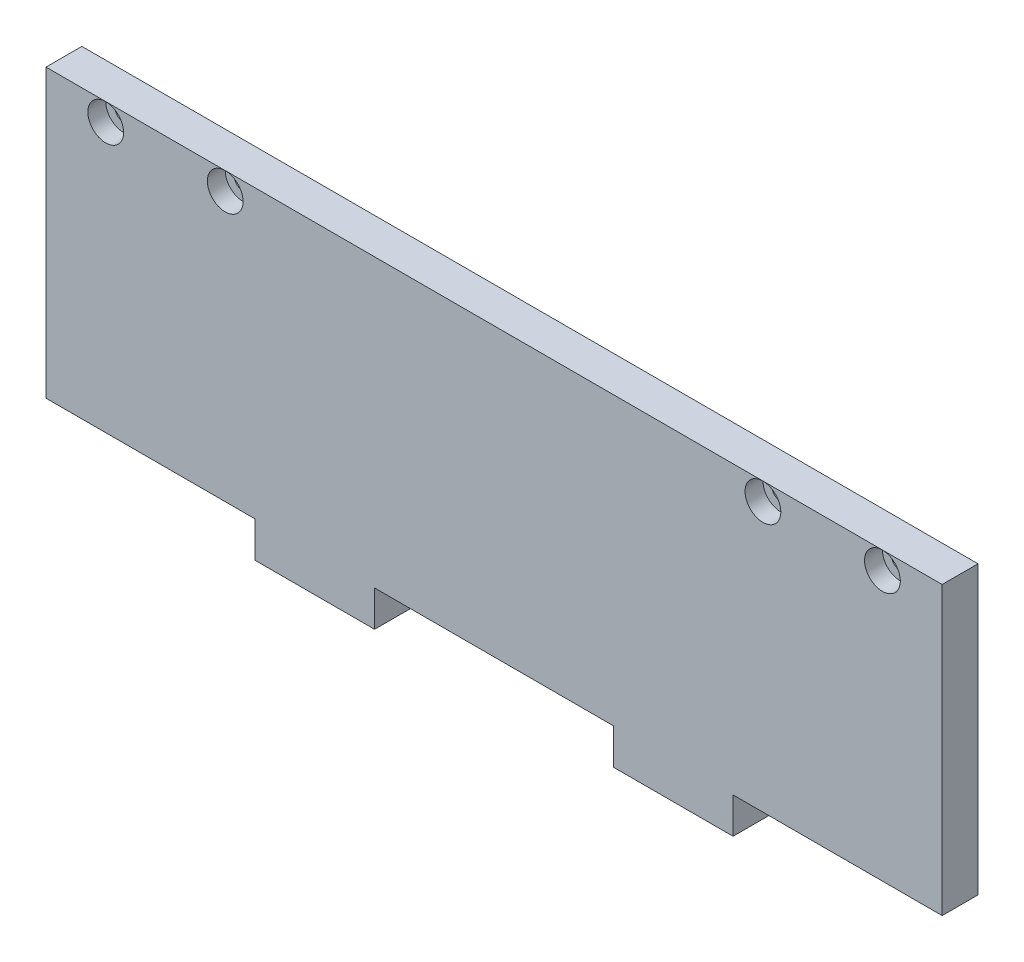
SolidWorks part; units mm, degrees
ref_plane "Plan de face" through (0, 0, 0) normal (0, 0, 1) x (1, 0, 0)
ref_plane "Plan de dessus" through (0, 0, 0) normal (0, 1, 0) x (1, 0, 0)
ref_plane "Plan de droite" through (0, 0, 0) normal (1, 0, 0) x (0, 0, -1)
sketch "Esquisse1" plane through (0, 0, 0) normal (0, 0, 1) x (1, 0, 0)
  line L1 (0, 0) -> (-150, 0)
  line L2 (0, 0) -> (0, 54)
  line L3 (0, 54) -> (-150, 54)
  line L4 (-150, 0) -> (-150, 54)
  dimension "D1" = 150
  dimension "D2" = 54
extrude "Boss.-Extru.1" add sketch "Esquisse1" along normal blind 6
sketch "Esquisse2" plane through (0, 0, 6) normal (0, 0, 1) x (1, 0, 0)
  line L1 (-150, 0) -> (0, 0) construction
  line L2 (0, 0) -> (-35, 0)
  line L3 (0, 0) -> (0, 6)
  line L4 (0, 6) -> (-35, 6)
  line L6 (-35, 0) -> (-35, 6)
  line L7 (-95, 0) -> (-55, 0)
  line L8 (-95, 0) -> (-95, 6)
  line L9 (-95, 6) -> (-55, 6)
  line L11 (-55, 0) -> (-55, 6)
  line L12 (-150, 0) -> (-115, 0)
  line L13 (-150, 0) -> (-150, 6)
  line L14 (-150, 6) -> (-115, 6)
  line L15 (-115, 0) -> (-115, 6)
  dimension "D1" = 6
  dimension "D2" = 20
  dimension "D3" = 20
  dimension "D4" = 6
  dimension "D5" = 6
  dimension "D6" = 35
  dimension "D7" = 35
extrude "Enlèv. mat.-Extru.1" cut sketch "Esquisse2" against normal through all
sketch "Esquisse4" plane through (0, 0, 6) normal (0, 0, 1) x (1, 0, 0)
  line L0 (0, 54) -> (-150, 54) construction
  line L1 (-150, 54) -> (-150, 6) construction
  line L2 (-75, 54) -> (-75, 6) construction
  line L3 (-55, 6) -> (-95, 6) construction
  circle A0 centre (-140, 51) radius 1.5
  circle A1 centre (-120, 51) radius 1.5
  circle A2 centre (-30, 51) radius 1.5
  circle A3 centre (-10, 51) radius 1.5
  dimension "D1" = 3
  dimension "D2" = 3
  dimension "D3" = 3
  dimension "D4" = 3
  dimension "D5" = 10
  dimension "D6" = 20
extrude "Enlèv. mat.-Extru.3" cut sketch "Esquisse4" against normal blind 6
sketch "Esquisse5" plane through (0, 0, 6) normal (0, 0, 1) x (1, 0, 0)
  line L0 (-75, 54) -> (-75, 6) construction
  line L1 (0, 54) -> (-150, 54) construction
  line L2 (-55, 6) -> (-95, 6) construction
  circle A0 centre (-140, 51) radius 2.995
  circle A1 centre (-120, 51) radius 2.995
  circle A2 centre (-30, 51) radius 2.995
  circle A3 centre (-10, 51) radius 2.995
  dimension "D1" = 5.99
  dimension "D2" = 5.99
extrude "Enlèv. mat.-Extru.4" cut sketch "Esquisse5" against normal blind 3
